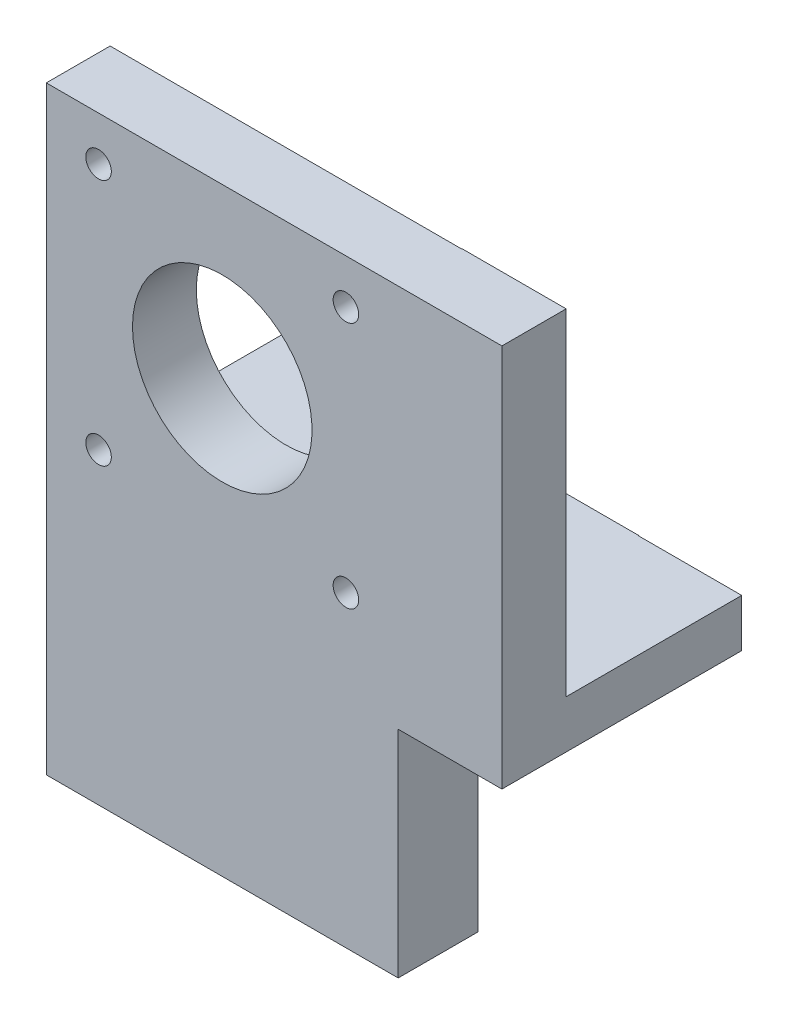
SolidWorks part; units mm, degrees
ref_plane "Front Plane" through (0, 0, 0) normal (0, 0, 1) x (1, 0, 0)
ref_plane "Top Plane" through (0, 0, 0) normal (0, 1, 0) x (1, 0, 0)
ref_plane "Right Plane" through (0, 0, 0) normal (1, 0, 0) x (0, 0, -1)
sketch "Sketch1" plane through (0, 0, 0) normal (0, 1, 0) x (1, 0, 0)
  line L1 (-8, 7.5) -> (8, 7.5) construction
  line L2 (-8, 7.5) -> (-8, -7.5) construction
  line L3 (-8, -7.5) -> (8, -7.5) construction
  line L4 (8, 7.5) -> (8, -7.5) construction
  line L5 (-8, 7.5) -> (8, -7.5) construction
  line L6 (-8, -7.5) -> (8, 7.5) construction
  line L7 (-22.05, 10.05) -> (22.05, 10.05) construction
  line L8 (-22.05, 10.05) -> (-22.05, -10.05) construction
  line L9 (-22.05, -10.05) -> (22.05, -10.05) construction
  line L10 (22.05, 10.05) -> (22.05, -10.05) construction
  line L11 (-22.05, 10.05) -> (22.05, -10.05) construction
  line L12 (-22.05, -10.05) -> (22.05, 10.05) construction
  line L13 (-22.05, -10.05) -> (22.05, -10.05) construction
  line L14 (-22.05, -10.05) -> (-22.05, -20.05) construction
  line L15 (-22.05, -20.05) -> (22.05, -20.05) construction
  line L16 (22.05, -10.05) -> (22.05, -20.05) construction
  point P0 (0, 0)
  point P1 (8, -7.5)
  point P2 (-8, 7.5)
  point P3 (-8, -7.5)
  point P4 (8, 7.5)
  point P6 (0, 0)
  point P18 (-8, 7.5)
  dimension "D1" = 16
  dimension "D2" = 15
  dimension "D3" = 20.1
  dimension "D4" = 44.1
  dimension "D5" = 10
sketch "Sketch3" plane through (0, 0, 0) normal (0, 1, 0) x (1, 0, 0)
  line L1 (-22.05, 10.05) -> (22.05, 10.05)
  line L2 (-22.05, 10.05) -> (-22.05, -20.05)
  line L3 (-22.05, -20.05) -> (22.05, -20.05)
  line L4 (22.05, 10.05) -> (22.05, -20.05)
extrude "Boss-Extrude1" add sketch "Sketch3" against normal blind 8
sketch "Sketch4" plane through (0, -8, 0) normal (0, -1, 0) x (1, 0, 0)
  line L1 (-22.05, 20.05) -> (22.05, 20.05)
  line L2 (-22.05, 20.05) -> (-22.05, 10.05)
  line L3 (-22.05, 10.05) -> (22.05, 10.05)
  line L4 (22.05, 20.05) -> (22.05, 10.05)
extrude "Boss-Extrude2" add sketch "Sketch4" along normal blind 25
sketch "Sketch8" plane through (0, 0, 0) normal (0, 1, 0) x (1, 0, 0)
  point P0 (8, -7.5)
  point P2 (-8, -7.5)
  point P4 (8, 7.5)
  point P6 (-8, 7.5)
hole_wizard "CSK for M3 Flat Head Machine Screw1" positions "Sketch8" profile "Sketch9" countersink size "M3" standard "ANSI Metric" end condition through all
sketch "Sketch9" plane through (8, 0, 7.5) normal (1, 0, 0) x (0, 0, 1)
  line L0 (0, 0) -> (0, 33)
  line L1 (0, 33) -> (1.6, 33)
  line L2 (1.6, 33) -> (1.6, 1.55)
  line L3 (1.6, 1.55) -> (3.15, 0)
  line L5 (3.15, 0) -> (0, 0)
  line L6 (-1.6, 1.55) -> (-3.15, 0) construction
  line L11 (0, -6.35) -> (0, 107.95) construction
  dimension "Thru Hole Dia." = 3.2
  dimension "Thru Hole Depth" = 33
  dimension "Near C'Sink Dia." = 6.3
  dimension "Near C'Sink Angle" = 90
sketch "Sketch10" plane through (0, 0, 0) normal (0, 1, 0) x (1, 0, 0)
  line L0 (-22.05, -10.05) -> (-22.05, -20.05) construction
  line L1 (-22.05, -12.05) -> (22.05, -12.05)
  line L2 (-22.05, -12.05) -> (-22.05, -20.05)
  line L3 (-22.05, -20.05) -> (22.05, -20.05)
  line L4 (22.05, -12.05) -> (22.05, -20.05)
  line L5 (22.05, -10.05) -> (22.05, -20.05) construction
  line L6 (-22.05, -10.05) -> (22.05, -10.05) construction
  dimension "D1" = 2
  dimension "D2" = 8
extrude "Boss-Extrude3" add sketch "Sketch10" along normal blind 42.1
sketch "Sketch11" plane through (0, 0, 12.05) normal (0, 0, -1) x (-1, 0, 0)
  line L0 (22.05, 21.05) -> (0, 21.05) construction
  line L1 (-15.5, 36.55) -> (15.5, 36.55) construction
  line L2 (-15.5, 36.55) -> (-15.5, 5.55) construction
  line L3 (-15.5, 5.55) -> (15.5, 5.55) construction
  line L4 (15.5, 36.55) -> (15.5, 5.55) construction
  line L5 (22.05, 42.1) -> (22.05, 0) construction
  line L6 (-22.05, 42.1) -> (22.05, 42.1) construction
  line L7 (0, 42.1) -> (0, 21.05) construction
  circle A0 centre (0, 21.05) radius 11.25
  point P9 (0, 42.1)
  point P10 (22.05, 21.05)
  point P13 (0, 36.55)
  point P16 (15.5, 21.05)
  dimension "D5" = 22.5
  dimension "D3" = 31
  dimension "D4" = 31
extrude "Cut-Extrude1" cut sketch "Sketch11" against normal blind 42
sketch "Sketch12" plane through (0, 0, 12.05) normal (0, 0, -1) x (-1, 0, 0)
  point P0 (15.5, 5.55)
  point P2 (-15.5, 5.55)
  point P4 (15.5, 36.55)
  point P6 (-15.5, 36.55)
hole_wizard "M3 Clearance Hole4" positions "Sketch12" profile "Sketch13" hole size "M3" standard "ANSI Metric" end condition through all
sketch "Sketch13" plane through (-15.5, 5.55, 12.05) normal (1, 0, 0) x (0, 1, 0)
  line L0 (0, 0) -> (0, 8)
  line L1 (0, 8) -> (1.6, 8)
  line L2 (1.6, 8) -> (1.6, 0)
  line L5 (1.6, 0) -> (0, 0)
  line L11 (0, -6.35) -> (0, 107.95) construction
  dimension "Thru Hole Dia." = 3.2
  dimension "Thru Hole Depth" = 8
sketch "Sketch14" plane through (22.05, 0, 0) normal (1, 0, 0) x (0, 0, -1)
  line L0 (10.05, 0) -> (-10.05, 0) construction
  line L1 (10, 0) -> (-10, 0)
  line L2 (10, 0) -> (10, -6)
  line L3 (10, -6) -> (-10, -6)
  line L5 (10.05, 0) -> (-10.05, 0) construction
  line L6 (-10, 0) -> (-12, 0)
  line L7 (-20.05, 42.1) -> (-12, 42.1)
  line L8 (-20.05, 42.1) -> (-20.05, -6)
  line L9 (-20.05, -6) -> (-12, -6)
  line L10 (-12, 42.1) -> (-12, 0)
  line L11 (-10.05, 0) -> (-20.05, 0) construction
  line L12 (-10, -6) -> (-12, -6)
  dimension "D1" = 6
  dimension "D2" = 20
extrude "Boss-Extrude4" add sketch "Sketch14" along normal blind 13
sketch "Sketch15" plane through (-22.05, 0, 0) normal (-1, 0, 0) x (0, 0, 1)
  line L8 (12.05, 0) -> (-10.05, 0)
  line L9 (-10.05, 0) -> (-10.05, -8)
  line L10 (-10.05, -8) -> (10.05, -8)
  line L11 (10.05, -8) -> (10.05, -33)
  line L12 (10.05, -33) -> (20.05, -33)
  line L13 (20.05, -33) -> (20.05, 42.1)
  line L14 (20.05, 42.1) -> (12.05, 42.1)
  line L15 (12.05, 42.1) -> (12.05, 0)
  line L16 (12.05, 0) -> (-10.05, 0)
  line L17 (-10.05, 0) -> (-10.05, -8)
  line L18 (-10.05, -8) -> (10.05, -8)
  line L19 (10.05, -8) -> (10.05, -33)
  line L20 (10.05, -33) -> (20.05, -33)
  line L21 (20.05, -33) -> (20.05, 42.1)
  line L22 (20.05, 42.1) -> (12.05, 42.1)
  line L23 (12.05, 42.1) -> (12.05, 0)
  dimension "D1" = 0
chamfer "Chamfer2" distance 2 angle 45 1 edges at (-22.05, -8, 0)
